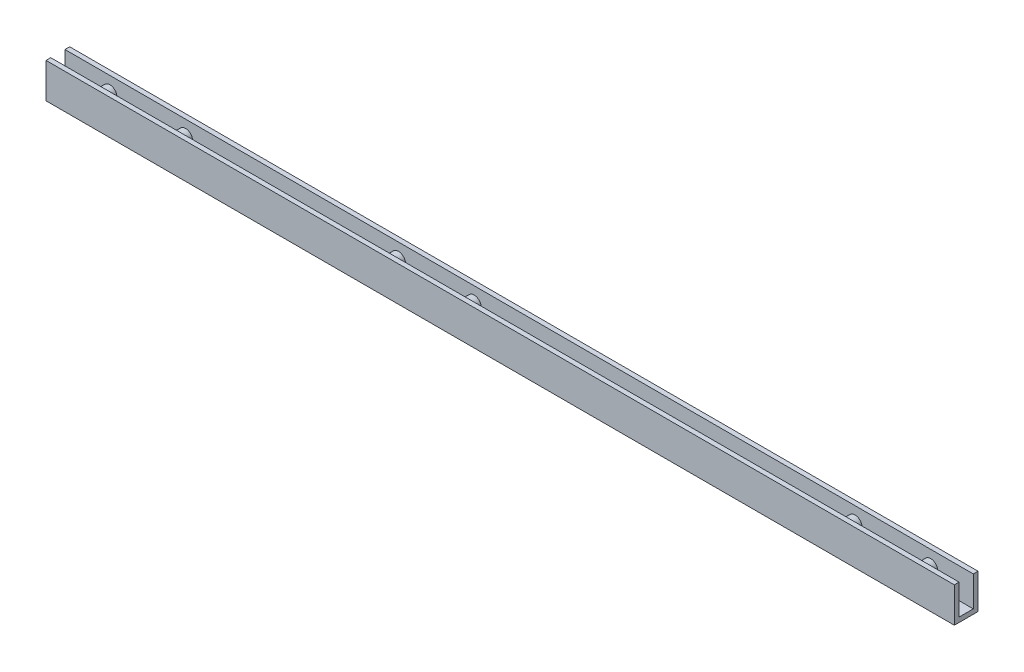
SolidWorks part; units mm, degrees
material "5052-O"
ref_plane "Front Plane" through (0, 0, 0) normal (0, 0, 1) x (1, 0, 0)
ref_plane "Top Plane" through (0, 0, 0) normal (0, 1, 0) x (1, 0, 0)
ref_plane "Right Plane" through (0, 0, 0) normal (1, 0, 0) x (0, 0, -1)
sketch "Sketch1" plane through (0, 0, 0) normal (1, 0, 0) x (0, 0, -1)
  line L0 (-4.7625, 7.0485) -> (-4.7625, 11.7475)
  line L1 (7.9375, -11.7475) -> (-7.9375, -11.7475)
  line L2 (7.9375, -11.7475) -> (7.9375, 11.7475)
  line L3 (-4.7625, 11.7475) -> (-7.9375, 11.7475)
  line L4 (-7.9375, -11.7475) -> (-7.9375, 11.7475)
  line L5 (7.9375, -11.7475) -> (-7.9375, 11.7475) construction
  line L6 (7.9375, 11.7475) -> (-7.9375, -11.7475) construction
  line L7 (4.7625, -8.5725) -> (-4.7625, -8.5725)
  line L8 (4.7625, -8.5725) -> (4.7625, 8.5725)
  line L10 (-4.7625, -8.5725) -> (-4.7625, 7.0485)
  line L12 (4.7625, 8.5725) -> (-4.7625, -8.5725) construction
  line L13 (4.7625, 8.5725) -> (4.7625, 11.7475)
  line L14 (4.7625, 11.7475) -> (7.9375, 11.7475)
  point P0 (0, 0)
  point P6 (0, 0)
  point P11 (4.4766, 10.9135)
  dimension "D1" = 3.175
  dimension "D2" = 3.175
  dimension "D3" = 3.175
  dimension "D4" = 15.875
  dimension "D5" = 20.32
extrude "Boss-Extrude1" add sketch "Sketch1" along normal blind 609.6
sketch "Sketch2" plane through (0, 0, 4.7625) normal (0, 0, 1) x (1, 0, 0)
  line L0 (0, 11.7475) -> (0, -11.7475) construction
  line L2 (0, 1.5875) -> (609.6, 1.5875) construction
  line L3 (0, -8.5725) -> (0, 11.7475) construction
  line L4 (609.6, 11.7475) -> (609.6, -11.7475) construction
  circle A0 centre (581.025, 1.5875) radius 4.7625
  circle A1 centre (530.225, 1.5875) radius 4.7625
  circle A2 centre (274.6375, 1.5875) radius 4.7625
  circle A3 centre (223.8375, 1.5875) radius 4.7625
  circle A4 centre (30.1625, 1.5875) radius 4.7625
  circle A5 centre (80.9625, 1.5875) radius 4.7625
  dimension "D1" = 9.525
  dimension "D2" = 50.8
  dimension "D3" = 50.8
  dimension "D4" = 50.8
  dimension "D5" = 30.1625
  dimension "D7" = 530.225
  dimension "D6" = 223.8375
extrude "Boss-Extrude5" add sketch "Sketch2" against normal up to surface (9.525 mm away) up to face at (304.8, 1.5875, -4.7625)
